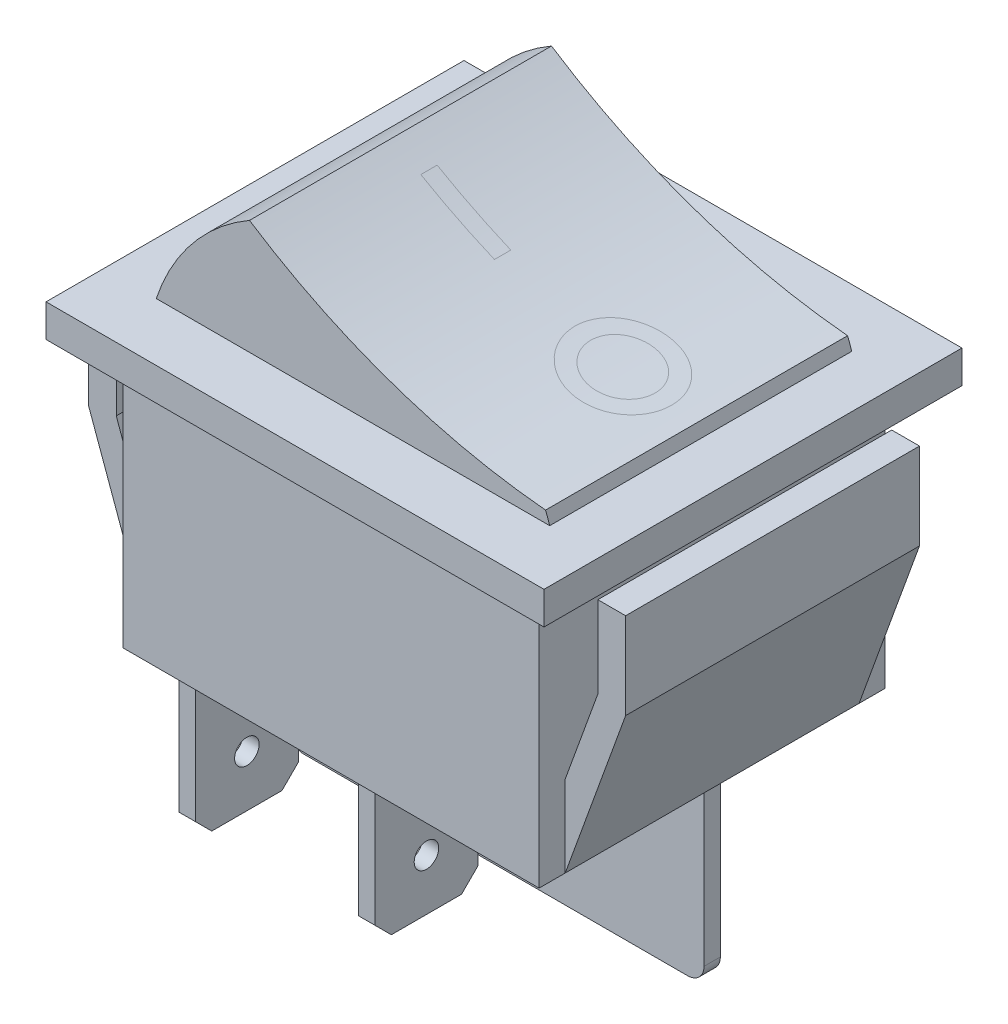
SolidWorks part; units mm, degrees
ref_plane "Front Plane" through (0, 0, 0) normal (0, 0, 1) x (1, 0, 0)
ref_plane "Top Plane" through (0, 0, 0) normal (0, 1, 0) x (1, 0, 0)
ref_plane "Right Plane" through (0, 0, 0) normal (1, 0, 0) x (0, 0, -1)
sketch "Sketch1" plane through (0, 0, 0) normal (0, 1, 0) x (1, 0, 0)
  line L0 (-12.75, 10.6) -> (12.75, -10.6) construction
  line L1 (-12.75, 10.6) -> (12.75, 10.6)
  line L2 (-12.75, 10.6) -> (-12.75, -10.6)
  line L3 (-12.75, -10.6) -> (12.75, -10.6)
  line L4 (12.75, 10.6) -> (12.75, -10.6)
  dimension "D1" = 21.2
  dimension "D2" = 25.5
extrude "Boss-Extrude1" add sketch "Sketch1" along normal blind 16.2
sketch "Sketch3" plane through (0, 16.2, 0) normal (0, 1, 0) x (1, 0, 0)
  line L0 (-15.25, 12.8) -> (15.25, -12.8) construction
  line L1 (-15.25, 12.8) -> (15.25, 12.8)
  line L2 (-15.25, 12.8) -> (-15.25, -12.8)
  line L3 (-15.25, -12.8) -> (15.25, -12.8)
  line L4 (15.25, 12.8) -> (15.25, -12.8)
  dimension "D1" = 25.6
  dimension "D2" = 30.5
extrude "Boss-Extrude2" add sketch "Sketch3" along normal blind 2
sketch "Sketch4" plane through (0, 0, 0) normal (0, 0, 1) x (1, 0, 0)
  line L0 (0, 16.2) -> (0, 14.2) construction
  line L1 (-15.25, 16.2) -> (15.25, 16.2) construction
  line L2 (-15.25, 18.2) -> (15.25, 18.2) construction
  line L3 (-12.05, 18.2) -> (12.05, 18.2)
  line L4 (-12.75, 16.2) -> (-12.75, 0) construction
  line L5 (0, 14.2) -> (2.3435, 20.9459) construction
  line L6 (0.1047, 21.7236) -> (2.3435, 20.9459) construction
  arc A0 (-6.3405, 25.2) -> (-12.05, 18.2) centre (0, 14.2) ccw
  arc A1 (-6.3405, 25.2) -> (11.7946, 18.9) centre (15.4696, 58.7308) ccw
  arc A2 (12.05, 18.2) -> (11.7946, 18.9) centre (0, 14.2) ccw
  dimension "D1" = 2
  dimension "D2" = 7
  dimension "D3" = 40
  dimension "D4" = 0.7
  dimension "D5" = 0.7
extrude "Boss-Extrude3" add sketch "Sketch4" along normal mid plane 18.5
ref_plane "Plane1" through (7.1288, 20.5209, 0) normal (-0.3282, -0.9446, 0) x (-0.9446, 0.3282, 0)
sketch "Sketch5" plane through (7.1288, 20.5209, 0) normal (-0.3282, -0.9446, 0) x (-0.9446, 0.3282, 0)
  line L0 (-4.9393, -9.25) -> (-0.4393, 0) construction
  line L1 (12.2589, -0.5) -> (7.2589, -0.5)
  line L2 (12.2589, -0.5) -> (12.2589, 0.5)
  line L3 (12.2589, 0.5) -> (7.2589, 0.5)
  line L4 (7.2589, -0.5) -> (7.2589, 0.5)
  line L5 (-0.4393, 0) -> (-4.9393, 9.25) construction
  line L6 (14.2589, -9.25) -> (12.2589, -0.5) construction
  line L7 (12.2589, 0.5) -> (14.2589, 9.25) construction
  line L8 (-0.4393, -2) -> (-0.4393, -3) construction
  line L9 (-4.9393, -9.25) -> (-4.9393, 9.25) construction
  line L10 (14.2589, -9.25) -> (14.2589, 9.25) construction
  circle A0 centre (-0.4393, 0) radius 3
  circle A1 centre (-0.4393, 0) radius 2
  dimension "D1" = 1
  dimension "D3" = 4
  dimension "D2" = 5
  dimension "D4" = 4.5
  dimension "D5" = 2
split line "Split Line1"
sketch "Sketch6" plane through (0, 0, 0) normal (1, 0, 0) x (0, 0, -1)
  line L0 (-8.4, 0) -> (-8.4, -9.2)
  line L1 (-10.6, 0) -> (10.6, 0) construction
  line L2 (-8.4, -9.2) -> (-7.4, -10.2)
  line L3 (-7.4, -10.2) -> (-3.1, -10.2)
  line L4 (-3.1, -10.2) -> (-2.1, -9.2)
  line L5 (-2.1, -9.2) -> (-2.1, 0)
  line L6 (-2.1, 0) -> (-8.4, 0)
  line L14 (-8.4, -7.05) -> (-5.25, -7.05) construction
  line L15 (-5.25, -7.05) -> (-5.25, -10.2) construction
  line L16 (0, 0) -> (0, -12.7241) construction
  line L17 (2.1, -9.2) -> (2.1, 0)
  line L18 (3.1, -10.2) -> (2.1, -9.2)
  line L19 (7.4, -10.2) -> (3.1, -10.2)
  line L20 (8.4, -9.2) -> (7.4, -10.2)
  line L21 (8.4, 0) -> (8.4, -9.2)
  line L22 (2.1, 0) -> (8.4, 0)
  circle A0 centre (-5.25, -7.05) radius 0.75
  circle A2 centre (5.25, -7.05) radius 0.75
  point P19 (-5.25, -10.2)
  dimension "D1" = 1
  dimension "D5" = 1.5
  dimension "D2" = 6.3
  dimension "D3" = 10.2
  dimension "D4" = 5.25
extrude "Boss-Extrude4" add sketch "Sketch6" along normal blind 0.5 and the other way blind 11.5
sketch "Sketch7" plane through (0, 0, 8.4) normal (0, 0, 1) x (1, 0, 0)
  line L0 (-11.5, 0) -> (0.5, 0) construction
  line L1 (-10.5, 0) -> (-0.5, 0)
  line L2 (-10.5, 0) -> (-10.5, -10.2)
  line L3 (-10.5, -10.2) -> (-0.5, -10.2)
  line L4 (-0.5, 0) -> (-0.5, -10.2)
  line L5 (-11.5, -10.2) -> (0.5, -10.2) construction
  line L6 (-11.5, 0) -> (-10.5, -10.2) construction
  line L7 (-0.5, -10.2) -> (0.5, 0) construction
  line L8 (-11.5, 0) -> (-11.5, -9.2) construction
  dimension "D1" = 1
extrude "Cut-Extrude1" cut sketch "Sketch7" against normal through all both and the other way through all
sketch "Sketch8" plane through (0, 0, 0) normal (0, 0, 1) x (1, 0, 0)
  line L0 (12.75, 16.2) -> (12.75, 0) construction
  line L1 (-12.75, 0) -> (12.75, 0)
  line L2 (-12.75, 0) -> (-12.75, -9.2)
  line L3 (-11.75, -10.2) -> (11.75, -10.2)
  line L4 (12.75, 0) -> (12.75, -9.2)
  line L5 (-0.5, -10.2) -> (0.5, -10.2) construction
  arc A0 (11.75, -10.2) -> (12.75, -9.2) centre (11.75, -9.2) ccw
  arc A1 (-12.75, -9.2) -> (-11.75, -10.2) centre (-11.75, -9.2) ccw
  dimension "D1" = 1
extrude "Boss-Extrude5" add sketch "Sketch8" along normal mid plane 1
sketch "Sketch9" plane through (0, 0, 0) normal (0, 0, 1) x (1, 0, 0)
  line L0 (-16.45, 15.5) -> (-14.75, 15.5)
  line L1 (-14.75, 15.5) -> (-14.75, 10.5)
  line L2 (-14.75, 10.5) -> (-12.75, 4.9858)
  line L3 (-12.75, 16.2) -> (-12.75, 0) construction
  line L4 (-12.75, 4.9858) -> (-12.75, 0)
  line L5 (-12.75, 0) -> (-16.45, 10.2012)
  line L6 (-16.45, 10.2012) -> (-16.45, 15.5)
  line L14 (-15.7195, 8.1871) -> (-14.1213, 8.7667) construction
  line L15 (-15.25, 18.2) -> (-15.25, 16.2) construction
  line L16 (-15.25, 16.2) -> (15.25, 16.2) construction
  line L17 (0, 0) -> (0, 16.2) construction
  line L18 (12.75, 0) -> (-12.75, 0) construction
  line L19 (-12.75, 16.2) -> (12.75, 16.2) construction
  line L20 (12.75, 0) -> (16.45, 10.2012)
  line L21 (12.75, 4.9858) -> (12.75, 0)
  line L22 (14.75, 10.5) -> (12.75, 4.9858)
  line L23 (14.75, 15.5) -> (14.75, 10.5)
  line L24 (16.45, 15.5) -> (14.75, 15.5)
  line L25 (16.45, 10.2012) -> (16.45, 15.5)
  dimension "D1" = 1.7
  dimension "D2" = 0.5
  dimension "D3" = 0.7
  dimension "D4" = 5
extrude "Boss-Extrude6" add sketch "Sketch9" along normal mid plane 18
